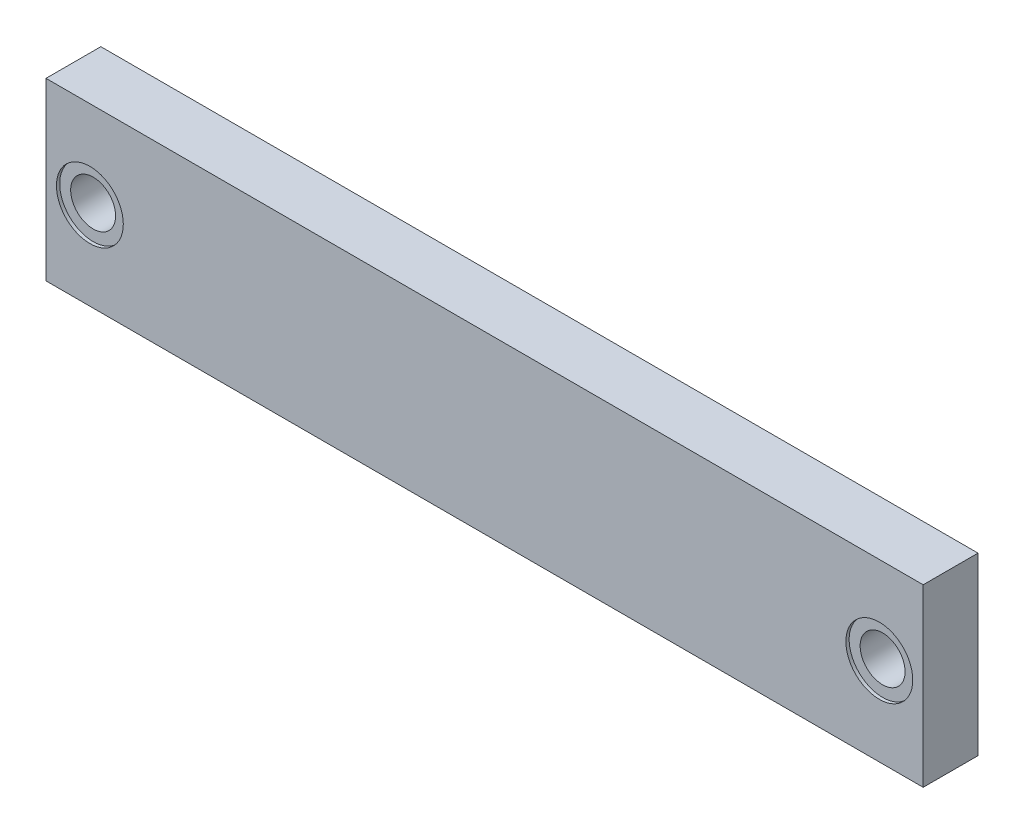
SolidWorks part; units mm, degrees
other "Elastomer Spring Installed Envelope"
ref_plane "Front Plane" through (0, 0, 0) normal (0, 0, 1) x (1, 0, 0)
ref_plane "Top Plane" through (0, 0, 0) normal (0, 1, 0) x (1, 0, 0)
ref_plane "Right Plane" through (0, 0, 0) normal (1, 0, 0) x (0, 0, -1)
sketch3d "Installed spring strip sketch datum points"
  point P0 (-40.2917, -20, 12.5)
  point P1 (-30.2917, -20, 12.5)
  point P2 (-40.2917, -10, 12.5)
ref_plane "Installed spring strip sketch plane" through (0, 0, 12.5) normal (0, 0, 1) x (1, 0, 0)
sketch "Installed spring strip sketch" plane through (0, 0, 12.5) normal (0, 0, 1) x (1, 0, 0)
  line L0 (-40.2917, -20) -> (39.7083, -20)
  line L1 (39.7083, -20) -> (39.7083, -4)
  line L2 (39.7083, -4) -> (-40.2917, -4)
  line L3 (-40.2917, -4) -> (-40.2917, -20)
extrude "Installed spring strip" add sketch "Installed spring strip sketch" along normal blind 5 separate body
sketch3d "Eyelet clearance 1 sketch datum points"
  point P0 (-36.2917, -12, 12.4)
  point P1 (-26.2917, -12, 12.4)
  point P2 (-36.2917, -2, 12.4)
ref_plane "Eyelet clearance 1 sketch plane" through (0, 0, 12.4) normal (0, 0, 1) x (1, 0, 0)
sketch "Eyelet clearance 1 sketch" plane through (0, 0, 12.4) normal (0, 0, 1) x (1, 0, 0)
  circle A0 centre (-36.2917, -12) radius 2.05
extrude "Eyelet clearance 1" cut sketch "Eyelet clearance 1 sketch" along normal blind 5.2
sketch3d "Flange recess 1-1 sketch datum points"
  point P0 (-36.2917, -12, 12.4)
  point P1 (-26.2917, -12, 12.4)
  point P2 (-36.2917, -2, 12.4)
ref_plane "Flange recess 1-1 sketch plane" through (0, 0, 12.4) normal (0, 0, 1) x (1, 0, 0)
sketch "Flange recess 1-1 sketch" plane through (0, 0, 12.4) normal (0, 0, 1) x (1, 0, 0)
  circle A0 centre (-36.2917, -12) radius 3.05
extrude "Flange recess 1-1" cut sketch "Flange recess 1-1 sketch" along normal blind 0.4
sketch3d "Flange recess 1-2 sketch datum points"
  point P0 (-36.2917, -12, 17.2)
  point P1 (-26.2917, -12, 17.2)
  point P2 (-36.2917, -2, 17.2)
ref_plane "Flange recess 1-2 sketch plane" through (0, 0, 17.2) normal (0, 0, 1) x (1, 0, 0)
sketch "Flange recess 1-2 sketch" plane through (0, 0, 17.2) normal (0, 0, 1) x (1, 0, 0)
  circle A0 centre (-36.2917, -12) radius 3.05
extrude "Flange recess 1-2" cut sketch "Flange recess 1-2 sketch" along normal blind 0.4
sketch3d "Eyelet clearance 2 sketch datum points"
  point P0 (35.7083, -12, 12.4)
  point P1 (45.7083, -12, 12.4)
  point P2 (35.7083, -2, 12.4)
ref_plane "Eyelet clearance 2 sketch plane" through (0, 0, 12.4) normal (0, 0, 1) x (1, 0, 0)
sketch "Eyelet clearance 2 sketch" plane through (0, 0, 12.4) normal (0, 0, 1) x (1, 0, 0)
  circle A0 centre (35.7083, -12) radius 2.05
extrude "Eyelet clearance 2" cut sketch "Eyelet clearance 2 sketch" along normal blind 5.2
sketch3d "Flange recess 2-1 sketch datum points"
  point P0 (35.7083, -12, 12.4)
  point P1 (45.7083, -12, 12.4)
  point P2 (35.7083, -2, 12.4)
ref_plane "Flange recess 2-1 sketch plane" through (0, 0, 12.4) normal (0, 0, 1) x (1, 0, 0)
sketch "Flange recess 2-1 sketch" plane through (0, 0, 12.4) normal (0, 0, 1) x (1, 0, 0)
  circle A0 centre (35.7083, -12) radius 3.05
extrude "Flange recess 2-1" cut sketch "Flange recess 2-1 sketch" along normal blind 0.4
sketch3d "Flange recess 2-2 sketch datum points"
  point P0 (35.7083, -12, 17.2)
  point P1 (45.7083, -12, 17.2)
  point P2 (35.7083, -2, 17.2)
ref_plane "Flange recess 2-2 sketch plane" through (0, 0, 17.2) normal (0, 0, 1) x (1, 0, 0)
sketch "Flange recess 2-2 sketch" plane through (0, 0, 17.2) normal (0, 0, 1) x (1, 0, 0)
  circle A0 centre (35.7083, -12) radius 3.05
extrude "Flange recess 2-2" cut sketch "Flange recess 2-2 sketch" along normal blind 0.4
